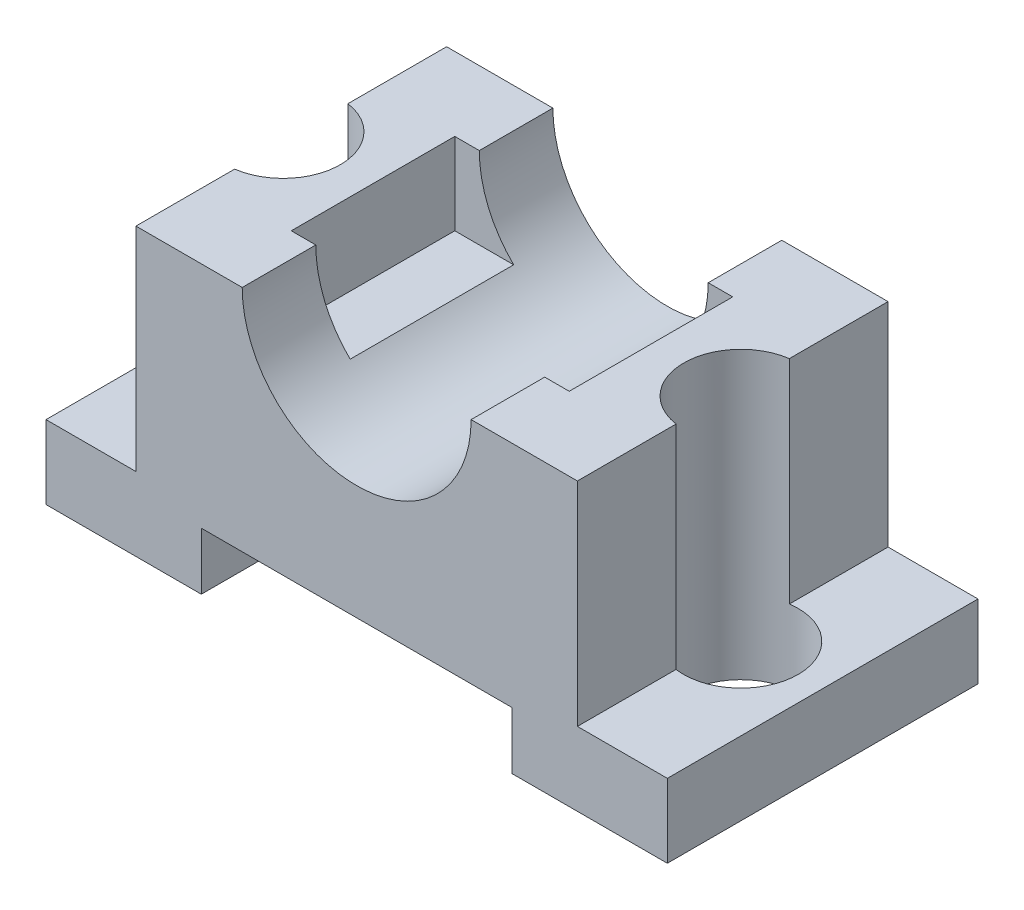
SolidWorks part; units mm, degrees
ref_plane "前视基准面" through (0, 0, 0) normal (0, 0, 1) x (1, 0, 0)
ref_plane "上视基准面" through (0, 0, 0) normal (0, 1, 0) x (1, 0, 0)
ref_plane "右视基准面" through (0, 0, 0) normal (1, 0, 0) x (0, 0, -1)
other "Configuration Table"
sketch "草图1" plane through (0, 0, 0) normal (0, 0, 1) x (1, 0, 0)
  line L0 (27, 9) -> (27, 35)
  line L2 (0, 0) -> (0, 7) construction
  line L3 (-19, 7) -> (19, 7)
  line L4 (19, 0) -> (19, 7)
  line L5 (19, 0) -> (38, 0)
  line L6 (19, 0) -> (19, 7)
  line L7 (27, 9) -> (38, 9)
  line L8 (38, 0) -> (38, 9)
  line L9 (27, 35) -> (14, 35)
  line L10 (-27, 35) -> (-14, 35)
  line L11 (-38, 0) -> (-38, 9)
  line L12 (-27, 9) -> (-38, 9)
  line L13 (-19, 0) -> (-19, 7)
  line L14 (-19, 0) -> (-38, 0)
  line L15 (-19, 0) -> (-19, 7)
  line L16 (-27, 9) -> (-27, 35)
  arc A0 (-14, 35) -> (14, 35) centre (0, 35) ccw
  dimension "D1" = 38
  dimension "D6" = 28
  dimension "D2" = 35
  dimension "D3" = 9
  dimension "D4" = 76
  dimension "D5" = 7
  dimension "D7" = 54
extrude "凸台-拉伸1" add sketch "草图1" along normal mid plane 38 contours A0 L10 L16 L12 L11 L14 L13 L3 L4 L5 L8 L7 L0 L9
sketch "草图2" plane through (0, 9, 0) normal (0, 1, 0) x (1, 0, 0)
  line L0 (0, 0) -> (46.1064, 0) construction
  line L1 (0, 0) -> (0, 22.9546) construction
  circle A0 centre (28, 0) radius 7
  circle A1 centre (-28, 0) radius 7
  dimension "D1" = 14
  dimension "D2" = 56
extrude "切除-拉伸1" cut sketch "草图2" against normal through all both and the other way through all
sketch "草图3" plane through (0, 35, 0) normal (0, 1, 0) x (1, 0, 0)
  line L1 (-17, -10) -> (17, -10)
  line L2 (-17, -10) -> (-17, 10)
  line L3 (-17, 10) -> (17, 10)
  line L4 (17, -10) -> (17, 10)
  line L5 (-17, -10) -> (17, 10) construction
  line L6 (-17, 10) -> (17, -10) construction
  point P0 (0, 0)
  dimension "D1" = 34
  dimension "D2" = 20
extrude "切除-拉伸2" cut sketch "草图3" against normal blind 10 and the other way through all
